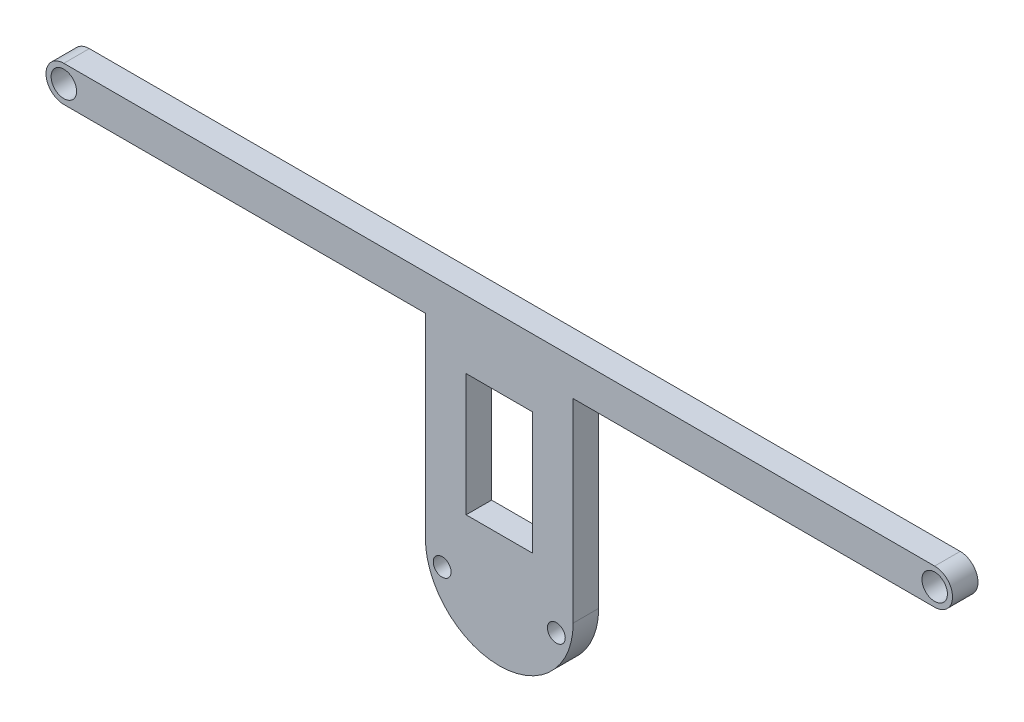
SolidWorks part; units mm, degrees
ref_plane "정면" through (0, 0, 0) normal (0, 0, 1) x (1, 0, 0)
ref_plane "윗면" through (0, 0, 0) normal (0, 1, 0) x (1, 0, 0)
ref_plane "우측면" through (0, 0, 0) normal (1, 0, 0) x (0, 0, -1)
sketch "스케치1" plane through (0, 0, 0) normal (0, 0, 1) x (1, 0, 0)
  line L0 (-85.42, 22.575) -> (85.42, 22.575)
  line L1 (-85.42, 19.075) -> (-85.42, -16.845) construction
  line L2 (-14.5, 15.575) -> (-14.5, -22.575)
  line L3 (-14.5, -22.575) -> (14.5, -22.575) construction
  line L4 (14.5, 15.575) -> (14.5, -22.575)
  line L5 (-6.5, 9.3238) -> (6.5, 9.3238) construction
  line L6 (6.5, 9.3238) -> (6.5, -14.6762) construction
  line L7 (0, 22.575) -> (0, -22.575) construction
  line L8 (6.5, -14.6762) -> (-6.5, -14.6762) construction
  line L9 (85.42, 19.075) -> (85.42, -16.845) construction
  line L10 (-14.5, -22.575) -> (0, -37.075) construction
  line L11 (-85.42, 15.575) -> (-14.5, 15.575)
  line L12 (0, -37.075) -> (14.5, -22.575) construction
  line L13 (-6.5, -14.6762) -> (-6.5, 9.3238) construction
  line L14 (-6.5, 9.3238) -> (6.5, 9.3238)
  line L15 (-6.5, -14.6762) -> (6.5, -14.6762)
  line L16 (-88.92, 19.075) -> (88.92, 19.075) construction
  line L17 (14.5, 15.575) -> (85.42, 15.575)
  line L18 (0, -14.6762) -> (-11.1994, -25.8756) construction
  line L19 (-6.5, 9.3238) -> (-6.5, -14.6762)
  line L20 (11.1994, -25.8756) -> (0, -14.6762) construction
  line L21 (6.5, 9.3238) -> (6.5, -14.6762)
  circle A0 centre (-85.42, 19.075) radius 2.5
  arc A1 (-85.42, 22.575) -> (-85.42, 15.575) centre (-85.42, 19.075) ccw
  arc A2 (85.42, 22.575) -> (85.42, 15.575) centre (85.42, 19.075) cw
  circle A3 centre (85.42, 19.075) radius 2.5
  arc A4 (-14.5, -22.575) -> (14.5, -22.575) centre (0, -22.575) ccw
  circle A5 centre (-11.1994, -25.8756) radius 1.75
  circle A6 centre (11.1994, -25.8756) radius 1.75
  point P0 (0, 0)
  point P5 (-88.92, 15.575)
  point P6 (88.92, 15.575)
  point P10 (-15, 22.575)
  point P11 (15, 22.575)
  point P16 (-88.92, 19.075)
  point P20 (88.92, 19.075)
  point P21 (0, 9.3238)
  point P26 (-85.42, 19.075)
  point P38 (0, -8.6762)
  dimension "D10" = 35.92
  dimension "D11" = 8.1688
  dimension "D1" = 45.15
  dimension "D3" = 8
  dimension "D4" = 18
  dimension "D2" = 13
  dimension "D5" = 15
  dimension "D6" = 15
  dimension "D7" = 28.3988
  dimension "D8" = 35.92
  dimension "D9" = 24
  dimension "D12" = 170.84
extrude "보스-돌출1" add sketch "스케치1" along normal blind 5
